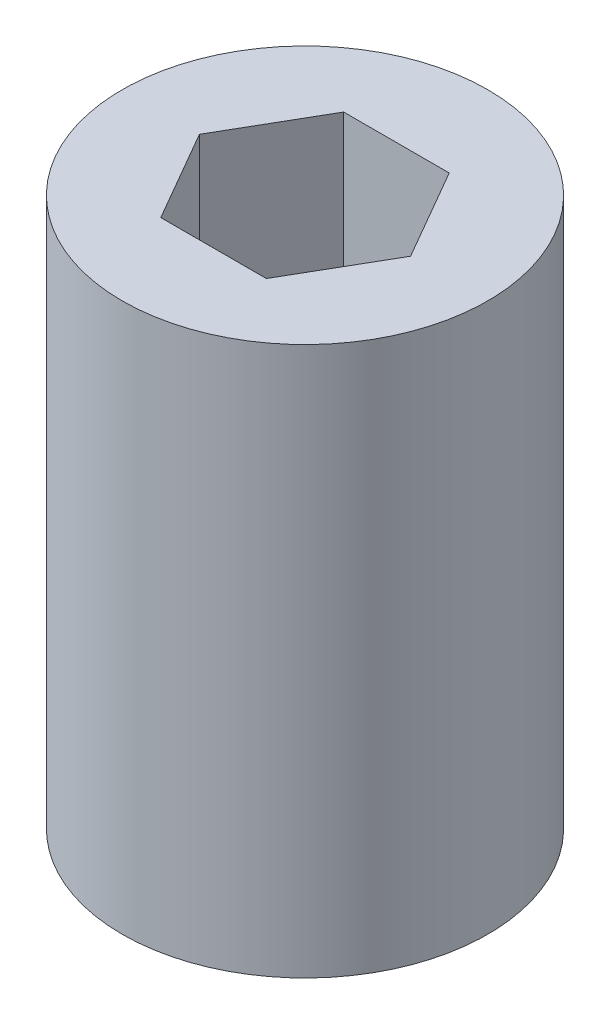
SolidWorks part; units mm, degrees
ref_plane "Front Plane" through (0, 0, 0) normal (0, 0, 1) x (1, 0, 0)
ref_plane "Top Plane" through (0, 0, 0) normal (0, 1, 0) x (1, 0, 0)
ref_plane "Right Plane" through (0, 0, 0) normal (1, 0, 0) x (0, 0, -1)
sketch "Sketch1" plane through (0, 0, 0) normal (0, 1, 0) x (1, 0, 0)
  line L1 (3.6662, -6.35) -> (7.3323, 0)
  line L2 (7.3323, 0) -> (3.6662, 6.35)
  line L3 (3.6662, 6.35) -> (-3.6662, 6.35)
  line L4 (-3.6662, 6.35) -> (-7.3323, 0)
  line L5 (-7.3323, 0) -> (-3.6662, -6.35)
  line L6 (-3.6662, -6.35) -> (3.6662, -6.35)
  circle A0 centre (0, 0) radius 6.35 construction
  circle A1 centre (0, 0) radius 12.7
  dimension "D2" = 25.4
  dimension "D1" = 12.7
extrude "Boss-Extrude1" add sketch "Sketch1" along normal blind 38.1
